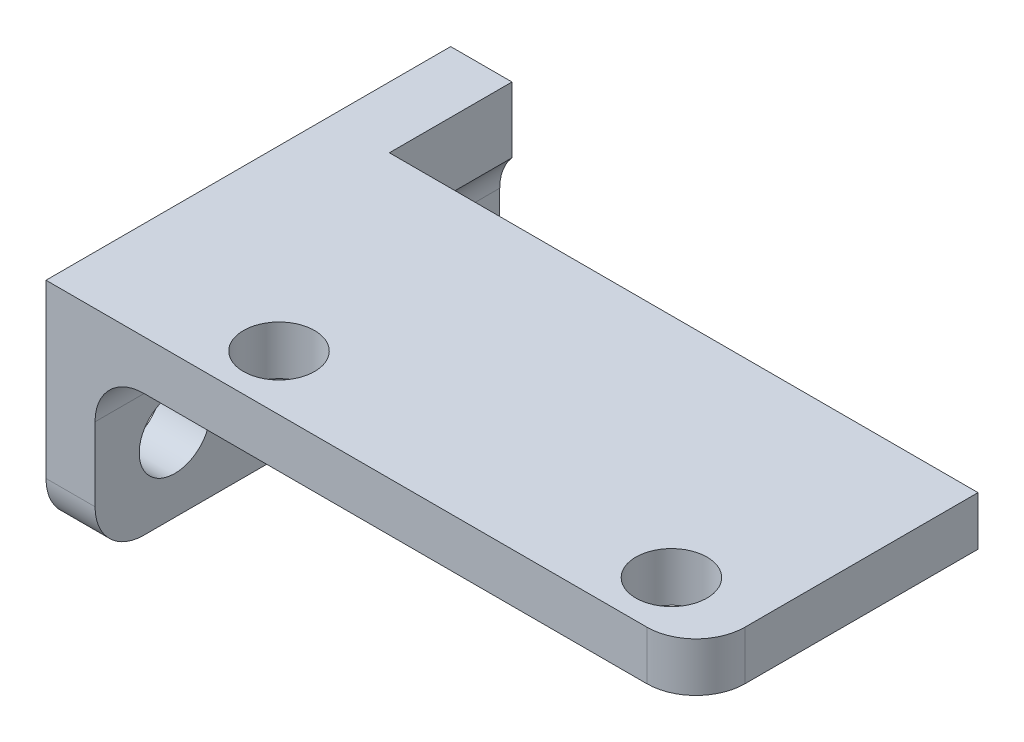
SolidWorks part; units mm, degrees
ref_plane "Alzado" through (0, 0, 0) normal (0, 0, 1) x (1, 0, 0)
ref_plane "Planta" through (0, 0, 0) normal (0, 1, 0) x (1, 0, 0)
ref_plane "Vista lateral" through (0, 0, 0) normal (1, 0, 0) x (0, 0, -1)
sketch "Croquis2" plane through (0, 0, 0) normal (0, 1, 0) x (1, 0, 0)
  line L0 (0, 8.25) -> (0, -8.25) construction
  line L1 (-11.25, -8.25) -> (11.25, -8.25) construction
  line L2 (-11.25, -8.25) -> (-11.25, 8.25) construction
  line L3 (-11.25, 8.25) -> (11.25, 8.25) construction
  line L4 (11.25, -8.25) -> (11.25, 8.25) construction
  line L5 (-11.25, -8.25) -> (11.25, 8.25) construction
  line L6 (-11.25, 8.25) -> (11.25, -8.25) construction
  line L10 (-11.25, 8.25) -> (11.25, 8.25)
  line L11 (11.25, 8.25) -> (11.25, -8.25)
  line L12 (11.25, -8.25) -> (-11.25, -8.25)
  line L13 (-11.25, 8.25) -> (-11.25, -8.25) construction
  line L14 (-11.25, 8.25) -> (-13.25, 8.25)
  line L15 (-13.25, 8.25) -> (-13.25, -8.25)
  line L16 (-13.25, -8.25) -> (-11.25, -8.25)
  circle A0 centre (-8, -6) radius 1.45
  circle A1 centre (8, -6) radius 1.45
  point P0 (0, 0)
  dimension "D4" = 2.25
  dimension "D5" = 2.9
  dimension "D6" = 2
  dimension "D1" = 22.5
  dimension "D2" = 16.5
  dimension "D3" = 3.25
extrude "Saliente-Extruir1" add sketch "Croquis2" along normal blind 2
sketch "Croquis3" plane through (-13.25, 0, 0) normal (-1, 0, 0) x (0, 0, 1)
  line L0 (0, 2) -> (0, 0) construction
  line L1 (-8.25, 2) -> (8.25, 2) construction
  line L3 (-8.25, 2) -> (8.25, 2)
  line L4 (-8.25, 2) -> (-8.25, -7)
  line L5 (-8.25, -7) -> (8.25, -7)
  line L6 (8.25, 2) -> (8.25, -7)
  circle A0 centre (-5, -4) radius 1.45
  circle A1 centre (5, -4) radius 1.45
  dimension "D1" = 2.9
  dimension "D2" = 5
  dimension "D3" = 3
  dimension "D4" = 9
  dimension "D5" = 16.5
extrude "Saliente-Extruir2" add sketch "Croquis3" along normal blind 2
fillet "Redondeo1" radius 2 1 edges at (-13.25, 0, 0)
fillet "Redondeo2" radius 2 4 edges at (-14.25, -7, 8.25) (-14.25, -7, -8.25) (11.25, 1, -8.25) (11.25, 1, 8.25)
sketch "Croquis4" plane through (0, 2, 0) normal (0, 1, 0) x (1, 0, 0)
  line L0 (9.25, 8.25) -> (-15.25, 8.25) construction
  line L1 (-12.75, 8.25) -> (11.25, 8.25)
  line L2 (-12.75, 8.25) -> (-12.75, 3.25)
  line L3 (-12.75, 3.25) -> (11.25, 3.25)
  line L4 (11.25, 8.25) -> (11.25, 3.25)
  line L5 (11.25, -6.25) -> (11.25, 6.25) construction
  line L6 (-15.25, -8.25) -> (-15.25, 8.25) construction
  dimension "D1" = 2.5
  dimension "D2" = 5
extrude "Cortar-Extruir1" cut sketch "Croquis4" against normal through all
